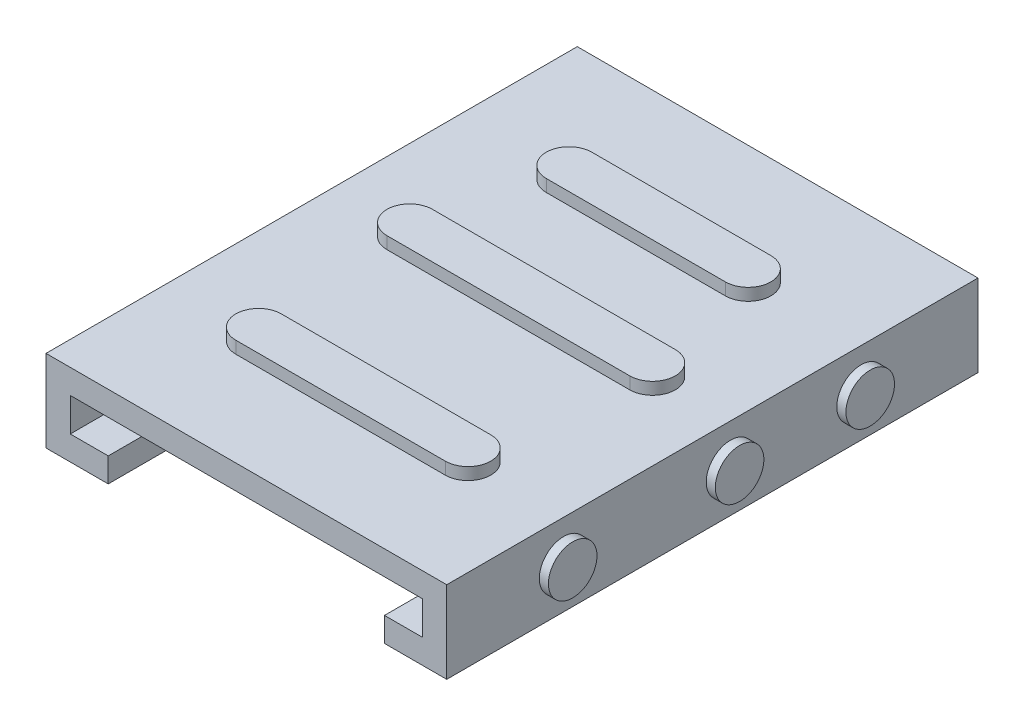
SolidWorks part; units mm, degrees
ref_plane "Front Plane" through (0, 0, 0) normal (0, 0, 1) x (1, 0, 0)
ref_plane "Top Plane" through (0, 0, 0) normal (0, 1, 0) x (1, 0, 0)
ref_plane "Right Plane" through (0, 0, 0) normal (1, 0, 0) x (0, 0, -1)
sketch "Sketch1" plane through (0, 0, 0) normal (0, 0, 1) x (1, 0, 0)
  line L0 (-59.8407, 7.2612) -> (-41.6407, 7.2612)
  line L30 (-62.3407, 7.2612) -> (-39.1407, 7.2612)
  line L34 (-62.3407, 7.2612) -> (-62.3407, 9.4612)
  line L36 (-62.3407, 9.4612) -> (-39.1407, 9.4612)
  line L37 (-39.1407, 7.2612) -> (-39.1407, 9.4612)
  line L38 (-50.7407, 9.4612) -> (-50.7407, 5.0275) construction
  line L39 (-59.8407, 7.2612) -> (-59.8407, 5.6612)
  line L40 (-59.8407, 5.6612) -> (-63.9407, 5.6612)
  line L41 (-63.9407, 5.6612) -> (-63.9407, 11.0612)
  line L42 (-63.9407, 11.0612) -> (-37.5407, 11.0612)
  line L43 (-37.5407, 11.0612) -> (-37.5407, 5.6612)
  line L44 (-37.5407, 5.6612) -> (-41.6407, 5.6612)
  line L45 (-41.6407, 5.6612) -> (-41.6407, 7.2612)
  dimension "D1" = 2.2
  dimension "D2" = 2.5
  dimension "D3" = 2.5
  dimension "D4" = 1.6
  dimension "D5" = 1.6
  dimension "D6" = 1.6
  dimension "D7" = 1.6
extrude "Boss-Extrude1" add sketch "Sketch1" along normal blind 35 contours L45 L44 L43 L42 L41 L40 L39 L30 L34 L36 L37
sketch "Sketch2" plane through (0, 11.0612, 0) normal (0, 1, 0) x (1, 0, 0)
  line L0 (-50.7407, 0) -> (-50.7407, -35) construction
  line L1 (-63.9407, 0) -> (-37.5407, 0) construction
  line L2 (-63.9407, -35) -> (-37.5407, -35) construction
  line L3 (-58.6263, -16.3536) -> (-42.6263, -16.3536) construction
  line L4 (-58.6263, -14.8536) -> (-42.6263, -14.8536)
  line L5 (-58.6263, -17.8536) -> (-42.6263, -17.8536)
  line L6 (-56.6407, -7.843) -> (-44.8407, -7.843) construction
  line L7 (-56.6407, -6.343) -> (-44.8407, -6.343)
  line L8 (-56.6407, -9.343) -> (-44.8407, -9.343)
  line L9 (-57.6407, -27.2963) -> (-43.8407, -27.2963) construction
  line L10 (-57.6407, -25.7963) -> (-43.8407, -25.7963)
  line L11 (-57.6407, -28.7963) -> (-43.8407, -28.7963)
  arc A0 (-58.6263, -14.8536) -> (-58.6263, -17.8536) centre (-58.6263, -16.3536) ccw
  arc A1 (-42.6263, -17.8536) -> (-42.6263, -14.8536) centre (-42.6263, -16.3536) ccw
  arc A2 (-56.6407, -6.343) -> (-56.6407, -9.343) centre (-56.6407, -7.843) ccw
  arc A3 (-44.8407, -9.343) -> (-44.8407, -6.343) centre (-44.8407, -7.843) ccw
  arc A4 (-57.6407, -25.7963) -> (-57.6407, -28.7963) centre (-57.6407, -27.2963) ccw
  arc A5 (-43.8407, -28.7963) -> (-43.8407, -25.7963) centre (-43.8407, -27.2963) ccw
  point P8 (-50.6263, -16.3536)
  point P13 (-50.7407, -7.843)
  point P20 (-50.7407, -27.2963)
extrude "Boss-Extrude2" add sketch "Sketch2" along normal blind 0.8 contours L8 A3 L7 A2 | L5 A1 L4 A0 | L11 A5 L10 A4
sketch "Sketch3" plane through (-63.9407, 0, 0) normal (-1, 0, 0) x (0, 0, 1)
  line L0 (0, 8.3612) -> (35, 8.3612) construction
  line L1 (0, 5.6612) -> (0, 11.0612) construction
  line L2 (35, 5.6612) -> (35, 11.0612) construction
  circle A0 centre (7.5265, 8.3612) radius 1.5
  circle A1 centre (16.4955, 8.3612) radius 1.5
  circle A2 centre (27.2583, 8.3612) radius 1.5
extrude "Boss-Extrude3" add sketch "Sketch3" along normal blind 0.6
sketch "Sketch5" plane through (-37.5407, 0, 0) normal (1, 0, 0) x (0, 0, -1)
  line L0 (-35, 11.0612) -> (-35, 5.6612) construction
  line L1 (0, 8.3612) -> (-35, 8.3612)
  line L2 (0, 11.0612) -> (0, 5.6612) construction
  circle A0 centre (-27.3017, 8.3612) radius 1.6
  circle A1 centre (-16.3052, 8.3612) radius 1.6
  circle A2 centre (-7.7015, 8.3612) radius 1.6
extrude "Boss-Extrude4" add sketch "Sketch5" along normal blind 0.6 contours A2 | A1 | A0
sketch "Sketch6" plane through (0, 5.6612, 0) normal (0, -1, 0) x (1, 0, 0)
  line L0 (-40.3801, 24.2088) -> (-38.3837, 24.2088)
  line L1 (-62.7119, 24.557) -> (-60.7155, 24.557)
  line L2 (-62.7119, 24.557) -> (-62.7119, 23.2106)
  line L3 (-62.7119, 23.2106) -> (-60.7155, 23.2106)
  line L4 (-60.7155, 24.557) -> (-60.7155, 23.2106)
  line L5 (-62.7119, 19.6821) -> (-60.7155, 19.6821)
  line L6 (-62.7119, 19.6821) -> (-62.7119, 18.3357)
  line L7 (-62.7119, 18.3357) -> (-60.7155, 18.3357)
  line L8 (-60.7155, 19.6821) -> (-60.7155, 18.3357)
  line L9 (-62.7119, 14.2501) -> (-60.7155, 14.2501)
  line L10 (-62.7119, 14.2501) -> (-62.7119, 12.9036)
  line L11 (-62.7119, 12.9036) -> (-60.7155, 12.9036)
  line L12 (-60.7155, 14.2501) -> (-60.7155, 12.9036)
  line L13 (-62.7119, 10.2573) -> (-60.6691, 10.2573)
  line L14 (-62.7119, 10.2573) -> (-62.7119, 8.9108)
  line L15 (-62.7119, 8.9108) -> (-60.6691, 8.9108)
  line L16 (-60.6691, 10.2573) -> (-60.6691, 8.9108)
  line L17 (-40.3801, 24.2088) -> (-40.3801, 22.8624)
  line L18 (-40.3801, 22.8624) -> (-38.3837, 22.8624)
  line L19 (-38.3837, 24.2088) -> (-38.3837, 22.8624)
  line L20 (-40.3801, 19.3339) -> (-38.3837, 19.3339)
  line L21 (-40.3801, 19.3339) -> (-40.3801, 17.9875)
  line L22 (-40.3801, 17.9875) -> (-38.3837, 17.9875)
  line L23 (-38.3837, 19.3339) -> (-38.3837, 17.9875)
  line L24 (-40.3801, 13.9018) -> (-38.3837, 13.9018)
  line L25 (-40.3801, 13.9018) -> (-40.3801, 12.5554)
  line L26 (-40.3801, 12.5554) -> (-38.3837, 12.5554)
  line L27 (-38.3837, 13.9018) -> (-38.3837, 12.5554)
  line L28 (-40.3801, 9.909) -> (-38.3373, 9.909)
  line L29 (-40.3801, 9.909) -> (-40.3801, 8.5626)
  line L30 (-40.3801, 8.5626) -> (-38.3373, 8.5626)
  line L31 (-38.3373, 9.909) -> (-38.3373, 8.5626)
extrude "Boss-Extrude5" add sketch "Sketch6" along normal blind 0.6
